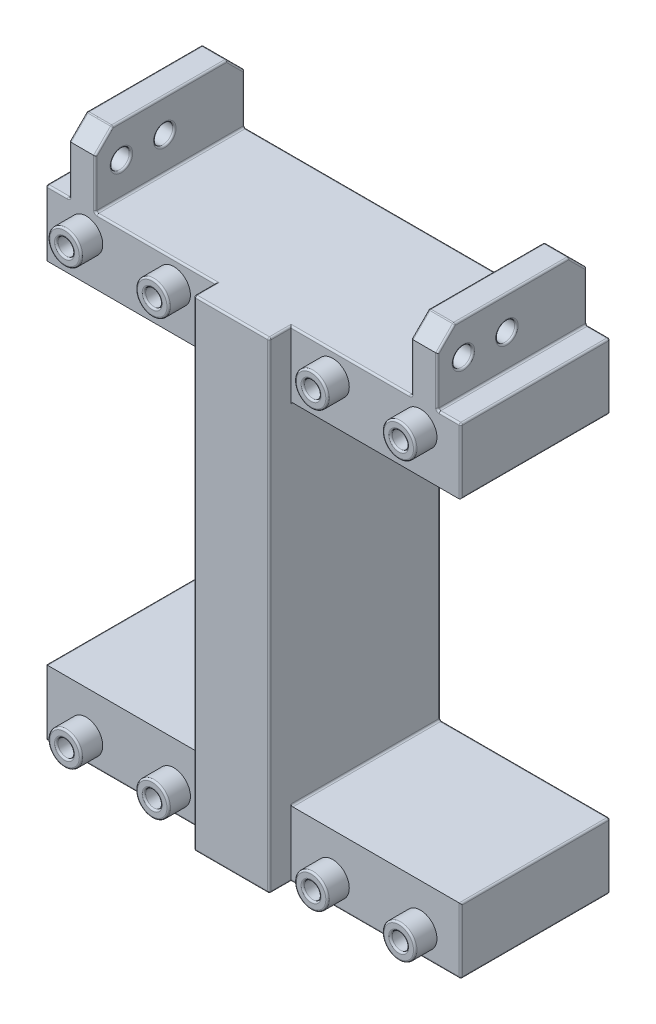
SolidWorks part; units mm, degrees
ref_plane "정면" through (0, 0, 0) normal (0, 0, 1) x (1, 0, 0)
ref_plane "윗면" through (0, 0, 0) normal (0, 1, 0) x (1, 0, 0)
ref_plane "우측면" through (0, 0, 0) normal (1, 0, 0) x (0, 0, -1)
sketch "스케치1" plane through (0, 0, 0) normal (0, 0, 1) x (1, 0, 0)
  line L0 (0, 0) -> (37.5737, 0) construction
  line L1 (4.5, -20) -> (4.5, 20)
  line L2 (4.5, 20) -> (23.9, 20)
  line L3 (4.5, -20) -> (23.9, -20)
  line L4 (23.9, 20) -> (23.9, 27.7)
  line L5 (23.9, -20) -> (23.9, -27.7)
  line L6 (23.9, 27.7) -> (-23.9, 27.7)
  line L7 (23.9, -27.7) -> (-23.9, -27.7)
  line L8 (0, -34.9912) -> (0, 34.9912) construction
  line L9 (-23.9, -20) -> (-23.9, -27.7)
  line L10 (-4.5, -20) -> (-23.9, -20)
  line L11 (-23.9, 20) -> (-23.9, 27.7)
  line L12 (-4.5, 20) -> (-23.9, 20)
  line L13 (-4.5, -20) -> (-4.5, 20)
  circle A0 centre (19.25, 25) radius 0.95
  circle A1 centre (19.25, -25) radius 0.95
  circle A2 centre (9.15, 25) radius 0.95
  circle A3 centre (9.15, -25) radius 0.95
  circle A4 centre (-9.15, -25) radius 0.95
  circle A5 centre (-19.25, -25) radius 0.95
  circle A6 centre (-19.25, 25) radius 0.95
  circle A7 centre (-9.15, 25) radius 0.95
  point P6 (4.5, 0)
  point P29 (0, -27.7)
  point P37 (0, 27.7)
  dimension "D5" = 1.9
  dimension "D7" = 4.65
  dimension "D8" = 10.1
  dimension "D1" = 40
  dimension "D2" = 19.4
  dimension "D3" = 4.5
  dimension "D4" = 7.7
  dimension "D6" = 2.7
extrude "보스-돌출1" add sketch "스케치1" along normal blind 8 and the other way blind 9.2 contours L13 L10 L9 L7 L5 L3 L1 L2 L4 L6 L11 L12 A6 A5 A4 A1 A0 A2 A3 A7
sketch "스케치2" plane through (0, 0, 8) normal (0, 0, 1) x (1, 0, 0)
  line L0 (23.9, 27.7) -> (-23.9, 27.7) construction
  circle A0 centre (0, 23.85) radius 1.5
  dimension "D1" = 3
  dimension "D2" = 3.85
sketch "스케치3" plane through (0, 0, 8) normal (0, 0, 1) x (1, 0, 0)
  circle A0 centre (-19.25, 25) radius 1.9
  circle A1 centre (-9.15, 25) radius 1.9
  circle A2 centre (9.15, 25) radius 1.9
  circle A3 centre (19.25, 25) radius 1.9
  circle A4 centre (-19.25, -25) radius 1.9
  circle A5 centre (-9.15, -25) radius 1.9
  circle A6 centre (9.15, -25) radius 1.9
  circle A7 centre (19.25, -25) radius 1.9
  circle A9 centre (19.25, -25) radius 0.95 construction
  circle A10 centre (9.15, -25) radius 0.95 construction
  circle A11 centre (-9.15, -25) radius 0.95 construction
  circle A12 centre (-19.25, -25) radius 0.95 construction
  circle A13 centre (19.25, 25) radius 0.95 construction
  circle A14 centre (9.15, 25) radius 0.95 construction
  circle A15 centre (-9.15, 25) radius 0.95 construction
  circle A16 centre (-19.25, 25) radius 0.95 construction
  circle A17 centre (19.25, -25) radius 0.95
  circle A18 centre (9.15, -25) radius 0.95
  circle A19 centre (-9.15, -25) radius 0.95
  circle A20 centre (-19.25, -25) radius 0.95
  circle A21 centre (19.25, 25) radius 0.95
  circle A22 centre (9.15, 25) radius 0.95
  circle A23 centre (-9.15, 25) radius 0.95
  circle A24 centre (-19.25, 25) radius 0.95
  dimension "D1" = 3.8
extrude "보스-돌출2" add sketch "스케치3" along normal blind 2.5 contours A0
sketch "스케치4" plane through (0, 0, 8) normal (0, 0, 1) x (1, 0, 0)
  line L0 (4.5, 20) -> (23.9, 20) construction
  line L1 (4.5, -20) -> (23.9, -20) construction
  line L2 (4.5, -20) -> (4.5, 20) construction
  line L3 (-4.5, -20) -> (-23.9, -20) construction
  line L4 (-4.5, -20) -> (-4.5, 20) construction
  line L5 (-4.5, 20) -> (-23.9, 20) construction
  line L6 (4.5, 20) -> (23.9, 20)
  line L7 (4.5, -20) -> (23.9, -20)
  line L8 (4.5, -20) -> (4.5, 20)
  line L9 (-4.5, -20) -> (-23.9, -20)
  line L10 (-4.5, -20) -> (-4.5, 20)
  line L11 (-4.5, 20) -> (-23.9, 20)
  line L13 (-23.9, 20) -> (-23.9, -20)
  line L14 (23.9, -20) -> (23.9, 20)
  line L15 (-4.35, 20.15) -> (-24.05, 20.15)
  line L16 (-24.05, 20.15) -> (-24.05, -20.15)
  line L17 (-4.35, -20.15) -> (-24.05, -20.15)
  line L18 (-4.35, -20.15) -> (-4.35, 20.15)
  line L19 (4.35, 20.15) -> (24.05, 20.15)
  line L20 (24.05, -20.15) -> (24.05, 20.15)
  line L21 (4.35, -20.15) -> (24.05, -20.15)
  line L22 (4.35, -20.15) -> (4.35, 20.15)
  line M13 (-4.5, 20) -> (-4.5, -20)
  line M14 (-4.5, -20) -> (-23.9, -20)
  line M15 (-23.9, -20) -> (-23.9, -27.7)
  line M17 (23.9, -27.7) -> (23.9, -20)
  line M18 (23.9, -20) -> (4.5, -20)
  line M19 (4.5, -20) -> (4.5, 20)
  line M20 (4.5, 20) -> (23.9, 20)
  line M21 (23.9, 20) -> (23.9, 27.7)
  line M23 (-23.9, 27.7) -> (-23.9, 20)
  line M24 (-23.9, 20) -> (-4.5, 20)
  dimension "D1" = 0.15
  dimension "D2" = 0.15
extrude "컷-돌출1" cut sketch "스케치4" against normal through all contours L17 L18 L15 M23 M24 M13 M14 M15 | L22 L21 L19 M17 M18 M19 M20 M21 | L11 L13 L9 L10
sketch "스케치5" plane through (0, 0, 8) normal (0, 0, 1) x (1, 0, 0)
  line L0 (0, 0) -> (0, 35.8829) construction
  line L1 (-4.35, 27.7) -> (4.35, 27.7)
  line L2 (23.9, 27.7) -> (-23.9, 27.7) construction
  line L3 (4.35, 27.7) -> (4.35, -27.7)
  line L4 (23.9, -27.7) -> (-23.9, -27.7) construction
  line L5 (-4.35, 27.7) -> (-4.35, -27.7)
  line L6 (4.35, -27.7) -> (-4.35, -27.7)
  line L7 (-4.35, -20.15) -> (-4.35, 20.15) construction
  point P8 (0, 27.7)
  point P13 (0, -27.7)
extrude "보스-돌출3" add sketch "스케치5" along normal blind 2.5 contours L5 L6 L3 L1
sketch "스케치6" plane through (23.9, 0, 0) normal (1, 0, 0) x (0, 0, -1)
  line L0 (9.2, -20.15) -> (9.2, -27.7) construction
  line L5 (0, 0) -> (-35.8802, 0) construction
  line L6 (-8, -31.54) -> (9.2, -31.54) construction
  line L7 (-8, -27.7) -> (9.2, -27.7)
  line L8 (-8, -27.7) -> (-8, -35.38)
  line L9 (-8, -35.38) -> (9.2, -35.38)
  line L10 (9.2, -27.7) -> (9.2, -35.38)
  line L12 (-8, 35.38) -> (9.2, 35.38)
  line L13 (9.2, 27.7) -> (9.2, 35.38)
  line L14 (-8, 27.7) -> (9.2, 27.7)
  line L15 (-8, 27.7) -> (-8, 35.38)
  circle A0 centre (-5, -31.54) radius 1.1
  circle A1 centre (0, -31.54) radius 1.1
  circle A2 centre (0, 31.54) radius 1.1
  circle A3 centre (-5, 31.54) radius 1.1
  dimension "D4" = 2.2
  dimension "D1" = 7.68
  dimension "D2" = 3
  dimension "D3" = 5
extrude "보스-돌출4" add sketch "스케치6" along normal blind 3 from offset 5.7 contours L15 L14 L13 L12 A2 A3 offset against normal yes
mirror "대칭 복사1" about plane through (0, 0, 0) normal (1, 0, 0) of "보스-돌출4"
chamfer "모따기1" distance 2 angle 45 4 edges at (19.7, 35.38, 8) (19.7, 35.38, -9.2) (-19.7, 35.38, -9.2) (-19.7, 35.38, 8)
fillet "필렛1" radius 0.2 106 edges at (-17.35, 25, 10.5) (10.1, -25, -9.2) (-18.3, 25, 10.5) (-8.2, 25, -9.2) (-7.25, 25, 10.5) (-8.2, 25, 10.5) (11.05, 25, 10.5) (10.1, 25, 10.5) (21.15, 25, 10.5) (20.2, 25, 10.5) (-17.35, -25, 10.5) (-18.3, -25, 10.5) (-7.25, -25, 10.5) (-8.2, -25, 10.5) (11.05, -25, 10.5) (10.1, -25, 10.5) (-18.3, 25, -9.2) (21.15, -25, 10.5) (20.2, -25, 10.5) (-23.9, 23.925, -9.2) (23.9, 23.925, -9.2) (23.9, -23.925, -9.2) (-23.9, -23.925, -9.2) (-23.9, -23.925, 8) (23.9, -23.925, 8) (23.9, 23.925, 8) (-23.9, 23.925, 8) (-4.35, -20.15, -0.6) (-23.9, -20.15, -0.6) (-14.125, 20.15, -9.2) (-23.9, 20.15, -0.6) (-4.35, 0, -9.2) (-4.35, 20.15, -0.6) (-14.125, -20.15, -9.2) (-18.3, -25, -9.2) (4.35, -20.15, -0.6) (4.35, 20.15, -0.6) (23.9, 20.15, -0.6) (14.125, -20.15, -9.2) (23.9, -20.15, -0.6) (4.35, 0, -9.2) (14.125, 20.15, -9.2) (-14.125, -27.7, 8) (-11.275, 27.7, 8) (0, 27.7, 10.5) (4.35, 27.7, 9.25) (-4.35, 27.7, 9.25) (0, -27.7, 10.5) (-4.35, -27.7, 9.25) (4.35, 0, 10.5) (4.35, -27.7, 9.25) (-4.35, 0, 10.5) (-8.2, -25, -9.2) (11.275, 27.7, 8) (0, 27.7, -9.2) (21.2, 30.54, 8) (18.2, 27.7, -0.6) (18.2, 30.54, -9.2) (18.2, 32.64, 0) (18.2, 32.64, 5) (21.2, 32.64, 0) (21.2, 27.7, -0.6) (21.2, 30.54, -9.2) (21.2, 32.64, 5) (18.2, 30.54, 8) (-22.55, 27.7, -9.2) (-22.55, 27.7, 8) (-18.2, 30.54, 8) (-21.2, 30.54, -9.2) (-21.2, 27.7, -0.6) (-21.2, 32.64, 0) (-21.2, 32.64, 5) (-21.2, 30.54, 8) (-18.2, 32.64, 0) (-18.2, 27.7, -0.6) (-18.2, 30.54, -9.2) (-18.2, 32.64, 5) (20.2, -25, -9.2) (18.2, 35.38, -0.6) (18.2, 34.38, -8.2) (18.2, 34.38, 7) (21.2, 35.38, -0.6) (19.7, 35.38, -7.2) (19.7, 35.38, 6) (21.2, 34.38, -8.2) (21.2, 34.38, 7) (-19.7, 33.38, -9.2) (19.7, 33.38, -9.2) (-18.2, 35.38, -0.6) (-21.2, 35.38, -0.6) (-19.7, 35.38, -7.2) (-19.7, 35.38, 6) (-18.2, 34.38, -8.2) (-18.2, 34.38, 7) (-21.2, 34.38, -8.2) (-21.2, 34.38, 7) (20.2, 25, -9.2) (-23.9, 27.7, -0.6) (23.9, 27.7, -0.6) (23.9, -27.7, -0.6) (-23.9, -27.7, -0.6) (14.125, -27.7, 8) (0, -27.7, -9.2) (22.55, 27.7, 8) (22.55, 27.7, -9.2) (10.1, 25, -9.2)
